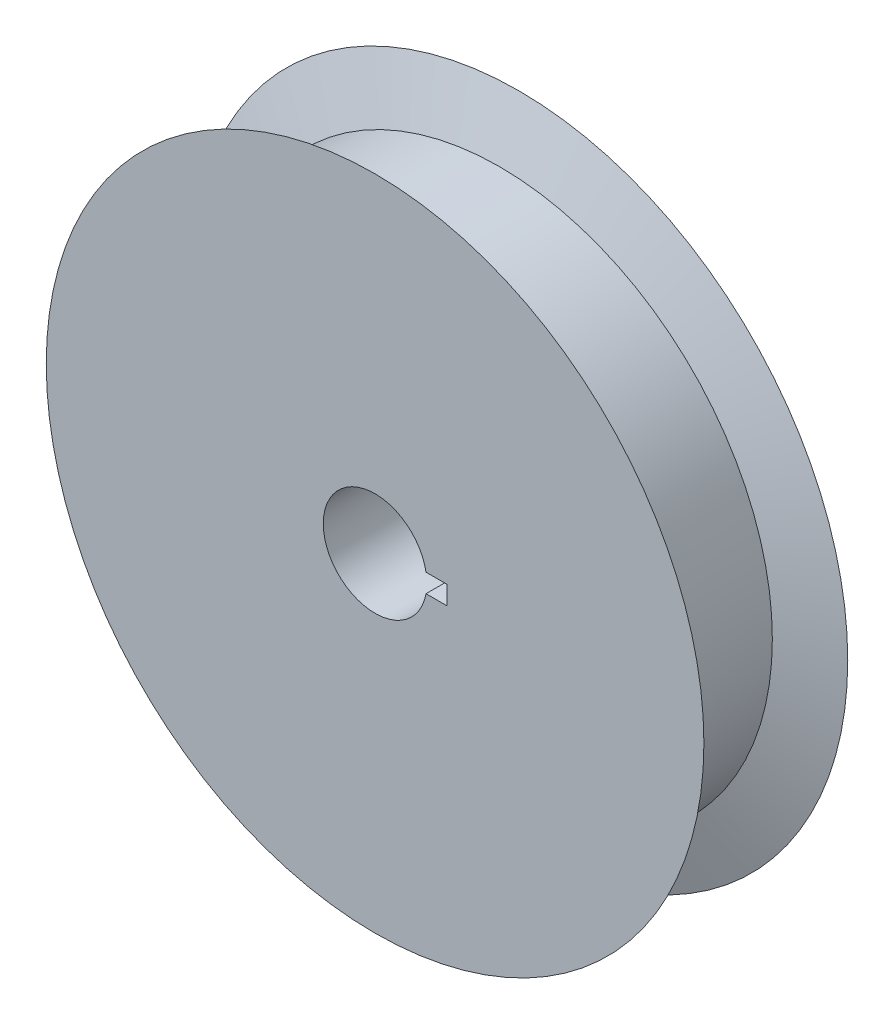
SolidWorks part; units mm, degrees
ref_plane "Front" through (0, 0, 0) normal (0, 0, 1) x (1, 0, 0)
ref_plane "Top" through (0, 0, 0) normal (0, 1, 0) x (1, 0, 0)
ref_plane "Right" through (0, 0, 0) normal (1, 0, 0) x (0, 0, -1)
sketch "Sketch1" plane through (0, 0, 0) normal (0, 0, 1) x (1, 0, 0)
  circle A0 centre (0, 0) radius 38.1
  dimension "D1" = 76.2
extrude "Boss-Extrude1" add sketch "Sketch1" along normal blind 16.6675
sketch "Sketch2" plane through (0, 0, 0) normal (0, 0, -1) x (-1, 0, 0)
  circle A0 centre (0, 0) radius 19.8438
  dimension "D1" = 39.6875
extrude "Boss-Extrude2" add sketch "Sketch2" along normal blind 11.1125
sketch "Sketch3" plane through (0, 0, -11.1125) normal (0, 0, -1) x (-1, 0, 0)
  line L1 (-5.9023, -1.0786) -> (-8.3153, -1.0786)
  line L3 (-5.9023, 1.0786) -> (-8.3153, 1.0786)
  line L4 (-8.3153, -1.0786) -> (-8.3153, 1.0786)
  arc A0 (-5.9023, -1.0786) -> (-5.9023, 1.0786) centre (0, 0) ccw
  dimension "D1" = 12
  dimension "D2" = 2.413
extrude "Cut-Extrude1" cut sketch "Sketch3" against normal through all
ref_plane "Plane1" through (0, -9.525, 0) normal (0, 1, 0) x (1, 0, 0)
sketch "Sketch5" plane through (0, -9.525, 0) normal (0, 1, 0) x (1, 0, 0)
  line L0 (19.8438, 11.1125) -> (-19.8438, 11.1125) construction
  circle A0 centre (0.5999, 5.5575) radius 3.2639
  dimension "D1" = 6.5278
  dimension "D2" = 5.555
extrude "Cut-Extrude2" cut sketch "Sketch5" against normal blind 11.1125 and the other way blind 11.1125
sketch "Sketch7" plane through (0, 0, 0) normal (1, 0, 0) x (0, 0, -1)
  line L0 (0, -38.1) -> (0, 38.1) construction
  line L1 (-16.6675, 38.1) -> (-16.6675, -38.1) construction
  line L2 (0, -38.1) -> (0, 38.1) construction
  line L3 (-16.6675, 38.1) -> (-16.6675, -38.1) construction
  line L5 (-16.6675, 38.1) -> (0, 38.1)
  line L6 (-16.6675, 0) -> (0, 0)
  line L7 (0, 38.1) -> (-2.2377, 31.6011)
  line L8 (-16.6675, 38.1) -> (-14.4297, 31.6011)
  line L9 (-14.4297, 31.6011) -> (-2.2377, 31.6011)
  point P2 (-8.3337, 31.6011)
  dimension "D1" = 38
  dimension "D2" = 12.192
  dimension "D3" = 8.3337
revolve "Cut-Revolve1" cut sketch "Sketch7" angle 360 about L6
